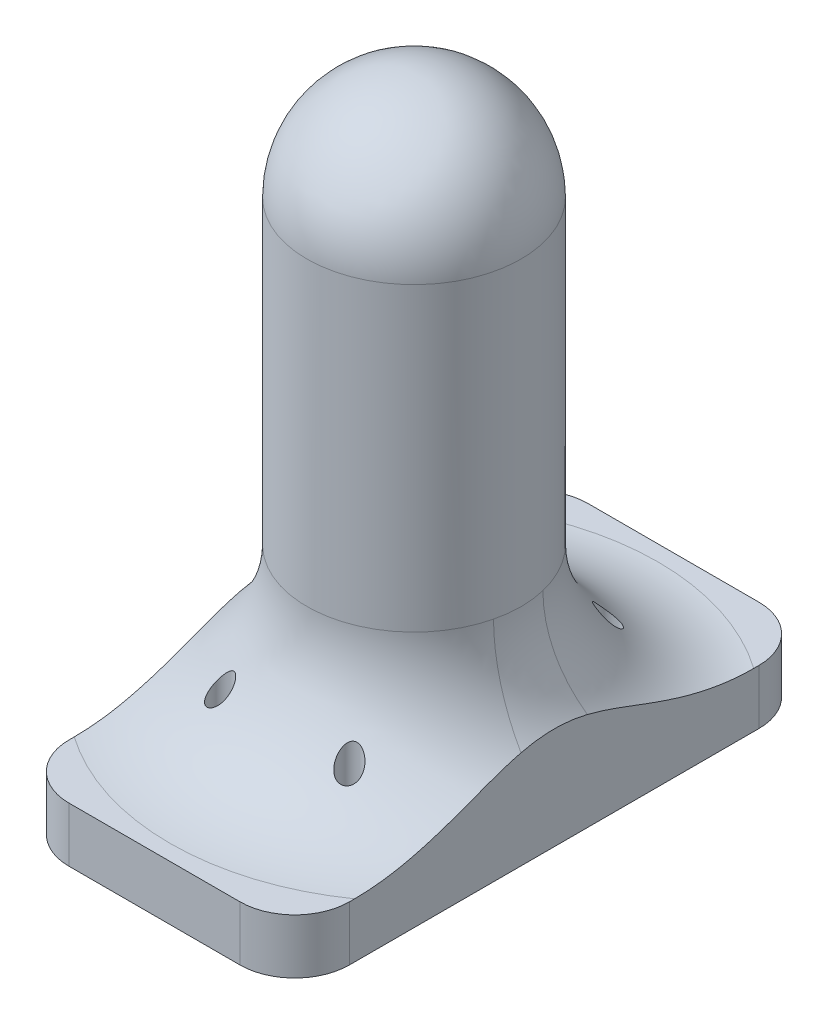
SolidWorks part; units mm, degrees
ref_plane "Front Plane" through (0, 0, 0) normal (0, 0, 1) x (1, 0, 0)
ref_plane "Top Plane" through (0, 0, 0) normal (0, 1, 0) x (1, 0, 0)
ref_plane "Right Plane" through (0, 0, 0) normal (1, 0, 0) x (0, 0, -1)
sketch "Sketch1" plane through (0, 0, 0) normal (0, 1, 0) x (1, 0, 0)
  line L1 (-22.0345, -24.0931) -> (22.0345, -24.0931)
  line L2 (-22.0345, -24.0931) -> (-22.0345, 24.0931)
  line L3 (-22.0345, 24.0931) -> (22.0345, 24.0931)
  line L4 (22.0345, -24.0931) -> (22.0345, 24.0931)
  line L5 (-22.0345, -24.0931) -> (22.0345, 24.0931) construction
  line L6 (-22.0345, 24.0931) -> (22.0345, -24.0931) construction
  point P0 (0, 0)
  dimension "D1" = 44.069
extrude "Boss-Extrude1" add sketch "Sketch1" along normal blind 5.08
sketch "Sketch2" plane through (0, 5.08, 0) normal (0, 1, 0) x (1, 0, 0)
  line L0 (0, 24.0931) -> (0, -24.0931) construction
  line L1 (22.0345, 24.0931) -> (-22.0345, 24.0931) construction
  line L2 (-22.0345, -24.0931) -> (22.0345, -24.0931) construction
  circle A0 centre (0, 0) radius 9.9441
  dimension "D1" = 19.8882
extrude "Boss-Extrude2" add sketch "Sketch2" along normal blind 40.64
sketch "Sketch3" plane through (0, 45.72, 0) normal (0, 1, 0) x (1, 0, 0)
  line L0 (0, 9.9441) -> (0, -9.9441) construction
  line L1 (0, 9.9441) -> (0, -9.9441)
  circle A0 centre (0, 0) radius 9.9441 construction
  arc A1 (0, -9.9441) -> (0, 9.9441) centre (0, 0) ccw
revolve "Revolve1" add sketch "Sketch3" angle 180 about L0
fillet "Fillet1" radius 12.7 1 edges at (0, 5.08, 9.9441)
sketch "Sketch4" plane through (0, 0, 0) normal (0, -1, 0) x (1, 0, 0)
  line L0 (-22.0345, 24.0931) -> (22.0345, 24.0931) construction
  line L1 (-7.9375, -24.0931) -> (7.9375, -24.0931)
  line L2 (-13.0175, -19.0131) -> (-13.0175, 19.0131)
  line L3 (-7.9375, 24.0931) -> (7.9375, 24.0931)
  line L4 (13.0175, -19.0131) -> (13.0175, 19.0131)
  line L5 (-13.0175, -24.0931) -> (13.0175, 24.0931) construction
  line L6 (-13.0175, 24.0931) -> (13.0175, -24.0931) construction
  line L11 (22.0345, -24.0931) -> (22.0345, 24.0931)
  line L12 (22.0345, 24.0931) -> (-22.0345, 24.0931)
  line L13 (-22.0345, 24.0931) -> (-22.0345, -24.0931)
  line L14 (-22.0345, -24.0931) -> (22.0345, -24.0931)
  line L15 (22.0345, -24.0931) -> (22.0345, 24.0931)
  line L16 (22.0345, 24.0931) -> (-22.0345, 24.0931)
  line L17 (-22.0345, 24.0931) -> (-22.0345, -24.0931)
  line L18 (-22.0345, -24.0931) -> (22.0345, -24.0931)
  arc A0 (-13.0175, -19.0131) -> (-7.9375, -24.0931) centre (-7.9375, -19.0131) ccw
  arc A1 (7.9375, -24.0931) -> (13.0175, -19.0131) centre (7.9375, -19.0131) ccw
  arc A2 (13.0175, 19.0131) -> (7.9375, 24.0931) centre (7.9375, 19.0131) ccw
  arc A3 (-7.9375, 24.0931) -> (-13.0175, 19.0131) centre (-7.9375, 19.0131) ccw
  point P0 (0, 0)
  line M13 (22.0345, -24.0931) -> (22.0345, 24.0931)
  line M14 (22.0345, 24.0931) -> (-22.0345, 24.0931)
  line M15 (-22.0345, 24.0931) -> (-22.0345, -24.0931)
  line M16 (-22.0345, -24.0931) -> (22.0345, -24.0931)
  dimension "D2" = 5.08
  dimension "D1" = 26.035
  dimension "D3" = 0
extrude "Cut-Extrude1" cut sketch "Sketch4" against normal through all contours A3 A0 L2 M14 M15 M16 | A2 L4 A1 M16 M13 M14
sketch "Sketch5" plane through (0, 0, 0) normal (0, -1, 0) x (1, 0, 0)
  line L0 (-13.0175, -19.0131) -> (-13.0175, 19.0131) construction
  arc A0 (-6, 13.3) -> (-6, 10.7) centre (-6, 12) ccw
  arc A1 (-6, 10.7) -> (-6, 13.3) centre (-6, 12) ccw
  arc A2 (6, 10.7808) -> (5.5769, 13.1434) centre (6, 12) ccw
  arc A3 (5.5769, 13.1434) -> (6, 10.7808) centre (6, 12) ccw
  arc A4 (2.25, -8) -> (4.75, -8) centre (3.5, -8) ccw
  arc A5 (4.75, -8) -> (2.25, -8) centre (3.5, -8) ccw
  arc A6 (8, 2.25) -> (8, 4.75) centre (8, 3.5) ccw
  arc A7 (8, 4.75) -> (8, 2.25) centre (8, 3.5) ccw
  arc A8 (-4.75, 8) -> (-2.25, 8) centre (-3.5, 8) ccw
  arc A9 (-2.25, 8) -> (-4.75, 8) centre (-3.5, 8) ccw
  arc A10 (-8, -4.75) -> (-8, -2.25) centre (-8, -3.5) ccw
  arc A11 (-8, -2.25) -> (-8, -4.75) centre (-8, -3.5) ccw
  arc A12 (0, -4.2) -> (0, 4.2) centre (0, 0) ccw
  arc A13 (0, 4.2) -> (0, -4.2) centre (0, 0) ccw
  arc A14 (6, -13.3) -> (6, -10.7) centre (6, -12) ccw
  arc A15 (6, -10.7) -> (6, -13.3) centre (6, -12) ccw
  arc A16 (-6, -13.3) -> (-6, -10.7) centre (-6, -12) ccw
  arc A17 (-6, -10.7) -> (-6, -13.3) centre (-6, -12) ccw
  arc A18 (-6, 10.7) -> (-6, 13.3) centre (-6, 12) cw
  arc A19 (-6, 13.3) -> (-6, 10.7) centre (-6, 12) cw
  arc A20 (6, 10.7808) -> (5.5769, 13.1434) centre (6, 12) cw
  arc A21 (5.5769, 13.1434) -> (6, 10.7808) centre (6, 12) cw
  arc A22 (-8, 2.25) -> (-8, 4.75) centre (-8, 3.5) cw
  arc A23 (-8, 4.75) -> (-8, 2.25) centre (-8, 3.5) cw
  arc A24 (-2.25, -8) -> (-4.75, -8) centre (-3.5, -8) cw
  arc A25 (-4.75, -8) -> (-2.25, -8) centre (-3.5, -8) cw
  arc A26 (8, -4.75) -> (8, -2.25) centre (8, -3.5) cw
  arc A27 (8, -2.25) -> (8, -4.75) centre (8, -3.5) cw
  arc A28 (4.75, 8) -> (2.25, 8) centre (3.5, 8) cw
  arc A29 (2.25, 8) -> (4.75, 8) centre (3.5, 8) cw
  arc A30 (6, -13.3) -> (6, -10.7) centre (6, -12) cw
  arc A31 (6, -10.7) -> (6, -13.3) centre (6, -12) cw
  arc A32 (-6, -10.7) -> (-6, -13.3) centre (-6, -12) cw
  arc A33 (-6, -13.3) -> (-6, -10.7) centre (-6, -12) cw
  dimension "D1" = 1.2192
  dimension "D2" = 1.3
  dimension "D3" = 1.25
  dimension "D4" = 4.2
  dimension "D5" = 5.0175
  dimension "D6" = 7.0175
  dimension "D7" = 9.5175
  dimension "D8" = 13.0175
  dimension "D9" = 16.5175
  dimension "D10" = 18.5944
  dimension "D11" = 19.0175
  dimension "D12" = 21.0175
  dimension "D13" = 5.8697
  dimension "D16" = 11.0131
  dimension "D17" = 15.5131
  dimension "D18" = 19.0131
  dimension "D19" = 22.5131
  dimension "D20" = 27.0131
  dimension "D21" = 31.0131
hole_wizard "M2.5x0.45 Tapped Hole1" positions "Sketch6" profile "Sketch7" tap size "M2.5x0.45" standard "ANSI Metric"
sketch "Sketch6" plane through (0, 0, 0) normal (0, -1, 0) x (-1, 0, 0)
  point P0 (-6, -12)
  point P3 (-3.5, -8)
  point P6 (-8, -3.5)
  point P9 (-8, 3.5)
  point P12 (-3.5, 8)
  point P15 (-6, 12)
  point P18 (3.5, 8)
  point P21 (6, 12)
  point P24 (8, 3.5)
  point P27 (8, -3.5)
  point P30 (3.5, -8)
  point P33 (6, -12)
sketch "Sketch7" plane through (6, 0, 12) normal (1, 0, 0) x (0, 0, -1)
  line L0 (0, 0) -> (0, 12.6159)
  line L1 (0, 12.6159) -> (1.025, 12)
  line L2 (1.025, 12) -> (1.025, 0)
  line L5 (1.025, 0) -> (0, 0)
  line L10 (0, 12.6159) -> (-1.025, 12) construction
  line L11 (0, -6.35) -> (0, 107.95) construction
  dimension "Tap Drill Dia." = 2.05
  dimension "Tap Drill Depth" = 12
  dimension "Drill Angle" = 118
cosmetic thread "Hole Thread1" parameters "D1"=5, "D2"=2.5
cosmetic thread "Hole Thread2" parameters "D1"=5, "D2"=2.5
cosmetic thread "Hole Thread3" parameters "D1"=5, "D2"=2.5
cosmetic thread "Hole Thread4" parameters "D1"=5, "D2"=2.5
cosmetic thread "Hole Thread5" parameters "D1"=5, "D2"=2.5
cosmetic thread "Hole Thread6" parameters "D1"=5, "D2"=2.5
cosmetic thread "Hole Thread7" parameters "D1"=5, "D2"=2.5
cosmetic thread "Hole Thread8" parameters "D1"=5, "D2"=2.5
cosmetic thread "Hole Thread9" parameters "D1"=5, "D2"=2.5
cosmetic thread "Hole Thread10" parameters "D1"=5, "D2"=2.5
cosmetic thread "Hole Thread11" parameters "D1"=5, "D2"=2.5
cosmetic thread "Hole Thread12" parameters "D1"=5, "D2"=2.5
extrude "Cut-Extrude2" cut sketch "Sketch5" against normal blind 10 contours A12 A13
